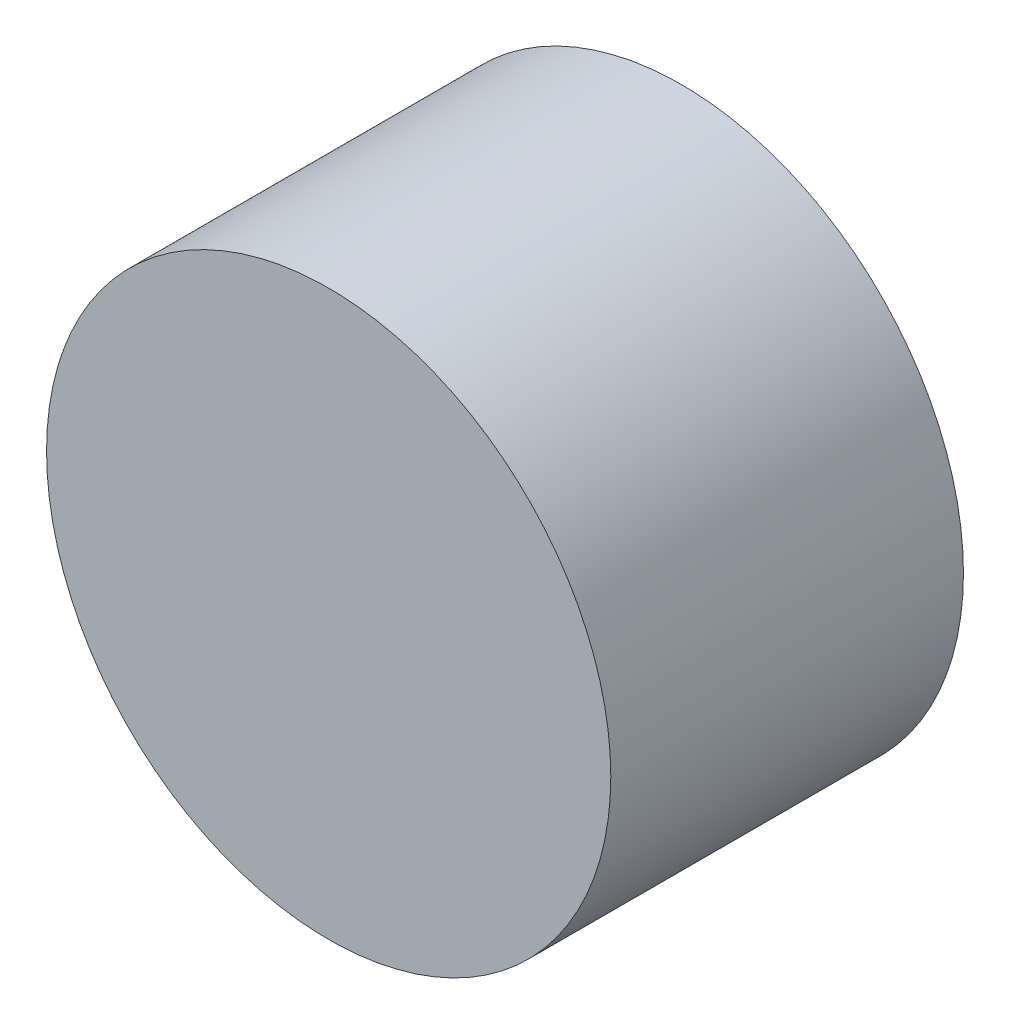
SolidWorks part; units mm, degrees
ref_plane "前视基准面" through (0, 0, 0) normal (0, 0, 1) x (1, 0, 0)
ref_plane "上视基准面" through (0, 0, 0) normal (0, 1, 0) x (1, 0, 0)
ref_plane "右视基准面" through (0, 0, 0) normal (1, 0, 0) x (0, 0, -1)
other "Configuration Table"
sketch "草图1" plane through (0, 0, 0) normal (0, 0, 1) x (1, 0, 0)
  circle A0 centre (0, 0) radius 6.5
extrude "凸台-拉伸1" add sketch "草图1" along normal blind 4 flip side to cut
sketch "草图2" plane through (0, 0, 0) normal (0, 0, -1) x (-1, 0, 0)
  circle A0 centre (0, 0) radius 3.2
extrude "切除-拉伸1" cut sketch "草图2" against normal blind 4 flip side to cut
